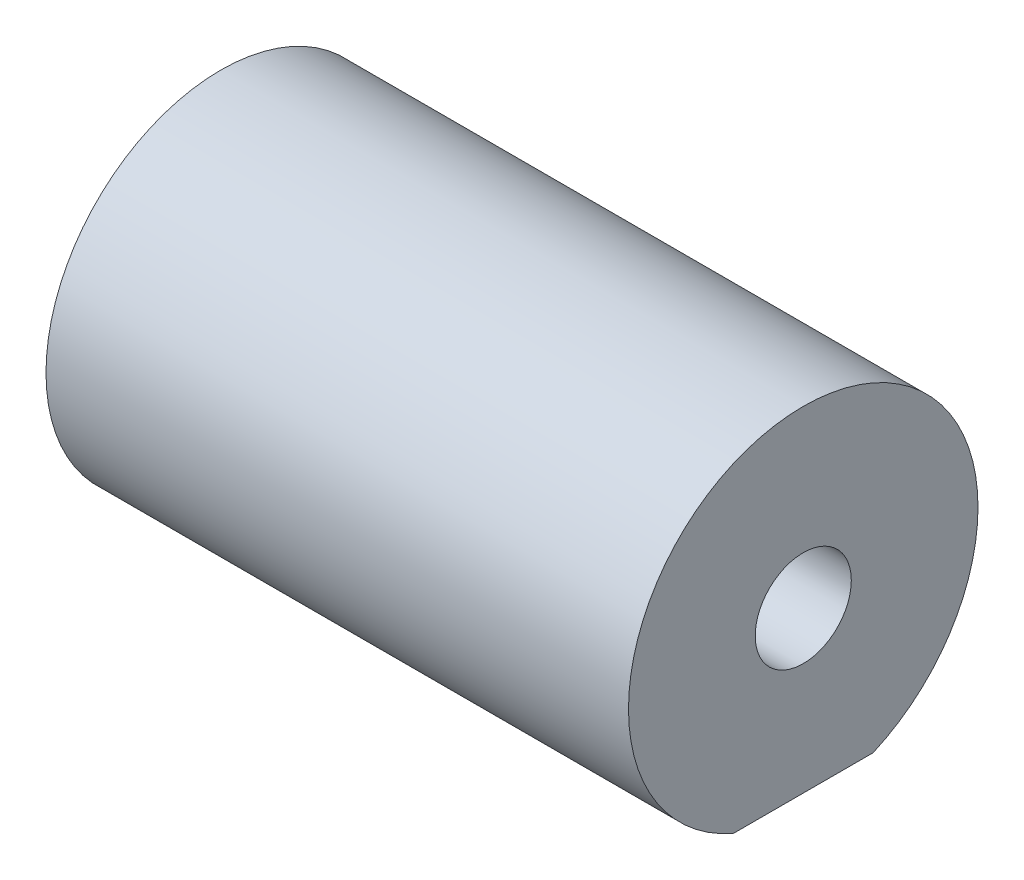
SolidWorks part; units mm, degrees
material "1060 合金"
ref_plane "正面" through (0, 0, 0) normal (0, 0, 1) x (1, 0, 0)
ref_plane "平面" through (0, 0, 0) normal (0, 1, 0) x (1, 0, 0)
ref_plane "右側面" through (0, 0, 0) normal (1, 0, 0) x (0, 0, -1)
sketch "ｽｹｯﾁ1" plane through (0, 0, 0) normal (1, 0, 0) x (0, 0, -1)
  circle A0 centre (0, 0) radius 6
  dimension "D1" = 12
extrude "ﾎﾞｽ - 押し出し1" add sketch "ｽｹｯﾁ1" along normal blind 20
sketch "ｽｹｯﾁ3" plane through (20, 0, 0) normal (1, 0, 0) x (0, 0, -1)
  circle A0 centre (0, 0) radius 1.65
  dimension "D1" = 3.3
extrude "ｶｯﾄ - 押し出し2" cut sketch "ｽｹｯﾁ3" against normal through all
sketch "ｽｹｯﾁ2" plane through (20, 0, 0) normal (1, 0, 0) x (0, 0, -1)
  line L0 (2.3979, -5.5) -> (-2.3979, -5.5)
  line L1 (0, 0) -> (0, -6) construction
  circle A0 centre (0, 0) radius 6
  circle M3 centre (0, 0) radius 6
  dimension "D1" = 12
  dimension "D2" = 5.5
extrude "ｶｯﾄ - 押し出し1" cut sketch "ｽｹｯﾁ2" against normal through all contours L0 L1 A0 | L1 L0 M3
